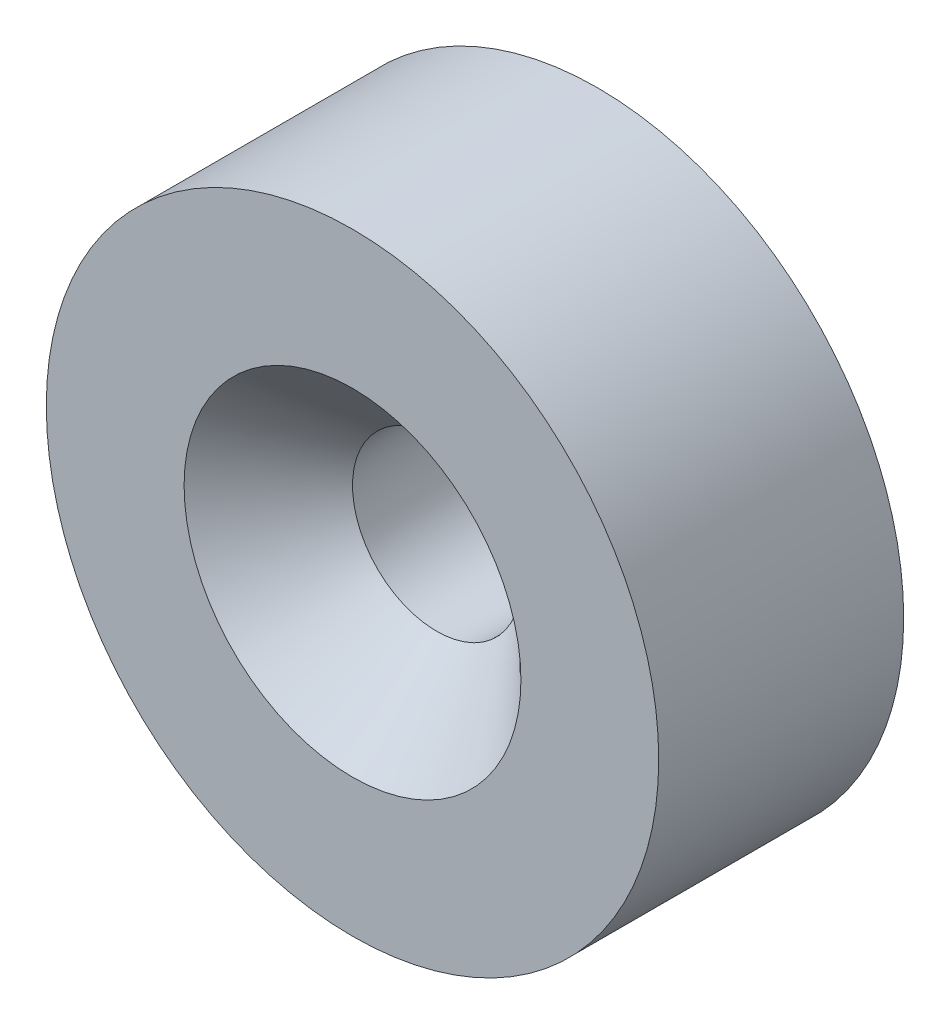
SolidWorks part; units mm, degrees
ref_plane "前视基准面" through (0, 0, 0) normal (0, 0, 1) x (1, 0, 0)
ref_plane "上视基准面" through (0, 0, 0) normal (0, 1, 0) x (1, 0, 0)
ref_plane "右视基准面" through (0, 0, 0) normal (1, 0, 0) x (0, 0, -1)
sketch "草图1" plane through (0, 0, 0) normal (0, 0, 1) x (1, 0, 0)
  circle A0 centre (0, 0) radius 10
  dimension "D1" = 20
extrude "凸台-拉伸1" add sketch "草图1" along normal blind 8
hole_wizard "打孔尺寸(%根据)内六角花形沉头螺钉的类型1" positions "草图2" profile "草图3" countersink size "M6" standard "GB"
sketch "草图2" plane through (0, 0, 8) normal (0, 0, 1) x (1, 0, 0)
  point P0 (0, 0)
sketch "草图3" plane through (0, 0, 8) normal (1, 0, 0) x (0, -1, 0)
  line L0 (0, 0) -> (0, 11.7524)
  line L1 (0, 11.7524) -> (2.75, 10.1)
  line L2 (2.75, 10.1) -> (2.75, 2.75)
  line L3 (2.75, 2.75) -> (5.5, 0)
  line L5 (5.5, 0) -> (0, 0)
  line L6 (-2.75, 2.75) -> (-5.5, 0) construction
  line L10 (0, 11.7524) -> (-2.75, 10.1) construction
  line L11 (0, -6.35) -> (0, 107.95) construction
  dimension "孔直径" = 5.5
  dimension "孔深度" = 10.1
  dimension "近端锥形沉头孔直径" = 11
  dimension "近端锥形沉头孔角度" = 90
  dimension "导头角度" = 118
